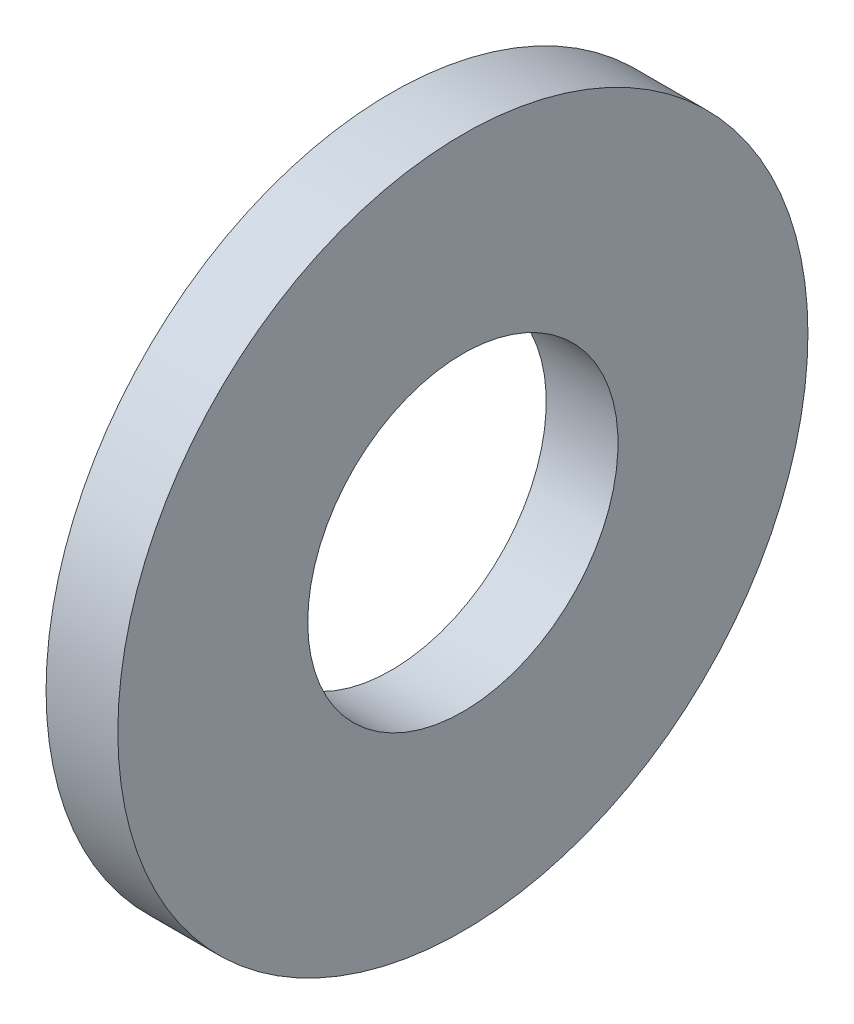
SolidWorks part; units mm, degrees
material "Chrome Stainless Steel"
ref_plane "Front Plane" through (0, 0, 0) normal (0, 0, 1) x (1, 0, 0)
ref_plane "Top Plane" through (0, 0, 0) normal (0, 1, 0) x (1, 0, 0)
ref_plane "Right Plane" through (0, 0, 0) normal (1, 0, 0) x (0, 0, -1)
ref_plane "Plane1" through (0, 0, 0) normal (0, 0, -1) x (-1, 0, 0)
sketch "Sketch1" plane through (0, 0, 0) normal (0, 0, -1) x (-1, 0, 0)
  line L0 (1.651, 7.9375) -> (0, 7.9375)
  line L1 (0, 7.9375) -> (0, 3.5687)
  line L2 (0, 3.5687) -> (1.651, 3.5687)
  line L3 (1.651, 3.5687) -> (1.651, 7.9375)
  line L4 (0, 0) -> (1.651, 0) construction
revolve "Revolve1" add sketch "Sketch1" angle 360 about L4
